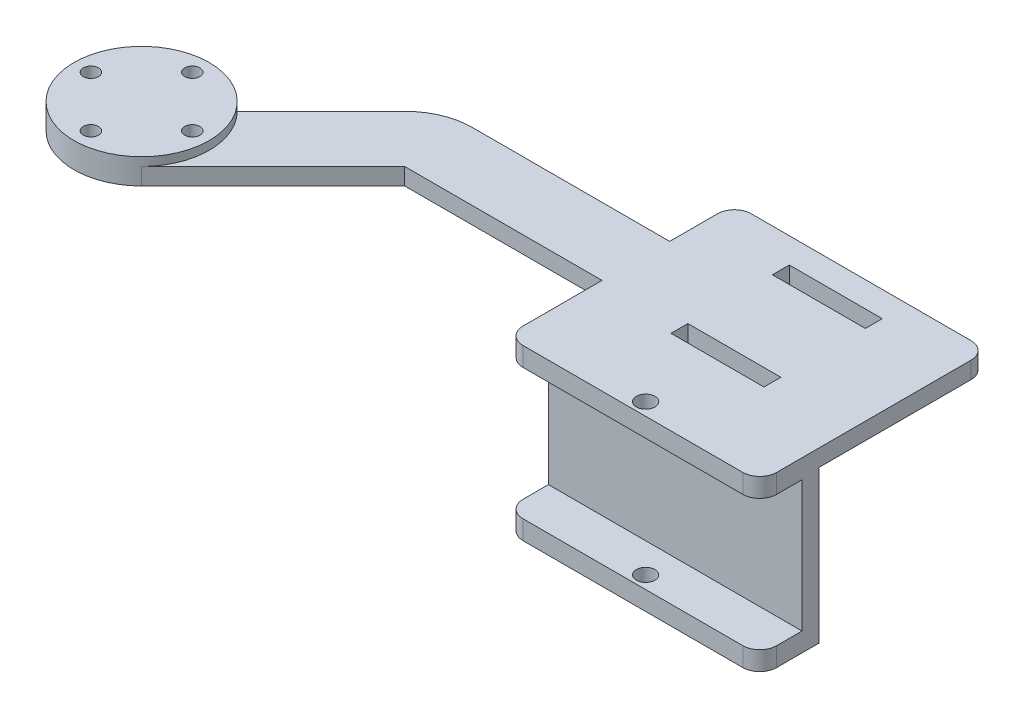
SolidWorks part; units mm, degrees
ref_plane "前视基准面" through (0, 0, 0) normal (0, 0, 1) x (1, 0, 0)
ref_plane "上视基准面" through (0, 0, 0) normal (0, 1, 0) x (1, 0, 0)
ref_plane "右视基准面" through (0, 0, 0) normal (1, 0, 0) x (0, 0, -1)
other "Configuration Table"
sketch "草图1" plane through (0, 0, 0) normal (0, 1, 0) x (1, 0, 0)
  line L1 (0, 0) -> (30, 0)
  line L2 (0, 0) -> (0, -7)
  line L3 (0, -7) -> (30, -7)
  line L4 (30, 0) -> (30, -7)
  dimension "D1" = 7
  dimension "D2" = 30
extrude "凸台-拉伸1" add sketch "草图1" along normal blind 20
sketch "草图2" plane through (0, 0, 7) normal (0, 0, 1) x (1, 0, 0)
  line L0 (0, 20) -> (0, 0) construction
  line L1 (0, 10) -> (6.5085, 10) construction
  line L2 (30, 20) -> (30, 0) construction
  line L3 (0, 17.75) -> (30, 17.75)
  line L4 (0, 17.75) -> (0, 2.25)
  line L5 (0, 2.25) -> (30, 2.25)
  line L6 (30, 17.75) -> (30, 2.25)
  line L7 (0, 17.75) -> (30, 2.25) construction
  point P4 (15, 10)
  point P12 (0, 10)
  dimension "D1" = 15.5
extrude "切除-拉伸1" cut sketch "草图2" against normal blind 5
sketch "草图4" plane through (0, 20, 0) normal (0, 1, 0) x (1, 0, 0)
  line L2 (0, -7) -> (30, -7) construction
  line L3 (30, 0) -> (0, 0) construction
  circle A3 centre (15, -5.5) radius 1.1
  point P0 (15, -7)
  point P1 (15, -5.5)
  dimension "D1" = 5.5
extrude "切除-拉伸2" cut sketch "草图4" against normal through all both and the other way through all
sketch "草图5" plane through (0, 0, 0) normal (0, 0, -1) x (-1, 0, 0)
  line L0 (-30, 20) -> (0, 20) construction
  line L1 (-30, 20) -> (0, 20)
  line L2 (-30, 20) -> (-30, 18)
  line L3 (-30, 18) -> (0, 18)
  line L4 (0, 20) -> (0, 18)
  line L5 (-30, 20) -> (-30, 0) construction
  line L6 (0, 20) -> (0, 0) construction
  dimension "D1" = 2
extrude "凸台-拉伸2" add sketch "草图5" along normal blind 20
sketch "草图6" plane through (0, 20, 0) normal (0, 1, 0) x (1, 0, 0)
  line L0 (0, 10) -> (30, 10) construction
  line L1 (0, 20) -> (0, -7) construction
  line L2 (30, -7) -> (30, 20) construction
  line L3 (0, 20) -> (30, 20) construction
  line L5 (9.5, 17) -> (20.5, 17)
  line L6 (9.5, 17) -> (9.5, 15)
  line L7 (9.5, 15) -> (20.5, 15)
  line L8 (20.5, 17) -> (20.5, 15)
  line L9 (9.5, 17) -> (20.5, 15) construction
  line L10 (9.5, 15) -> (20.5, 17) construction
  line L11 (9.5, 5) -> (20.5, 5)
  line L12 (9.5, 5) -> (9.5, 3)
  line L13 (9.5, 3) -> (20.5, 3)
  line L14 (20.5, 5) -> (20.5, 3)
  line L15 (9.5, 5) -> (20.5, 3) construction
  line L16 (9.5, 3) -> (20.5, 5) construction
  point P8 (15, 16)
  point P9 (15, 4)
  point P10 (15, 16)
  point P15 (15, 4)
  dimension "D1" = 10
  dimension "D2" = 6
  dimension "D3" = 6
  dimension "D4" = 2
  dimension "D5" = 11
  dimension "D6" = 11
  dimension "D7" = 2
extrude "切除-拉伸3" cut sketch "草图6" against normal up to surface (2 mm away) up to face at (15, 18, -10)
sketch "草图7" plane through (0, 18, 0) normal (0, -1, 0) x (1, 0, 0)
  line L0 (0, -20) -> (0, 0) construction
  line L1 (0, -10) -> (0, -12.3431)
  line L2 (0, -10) -> (0, -4.3431)
  line L3 (0, -10) -> (-29, -10) construction
  line L4 (-29, -10) -> (-44.5, -10) construction
  line L5 (-29, -10) -> (-23.3431, -4.3431) construction
  line L6 (0, -12.3431) -> (-23.3431, -12.3431)
  line L7 (0, -12.3431) -> (0, -4.3431)
  line L8 (0, -4.3431) -> (-23.3431, -4.3431)
  line L9 (-23.3431, -12.3431) -> (-23.3431, -4.3431) construction
  line L10 (-44.5, -10) -> (-44.5, 11.6178) construction
  line L11 (-23.3431, -4.3431) -> (-29, -10) construction
  line L12 (-23.3431, -4.3431) -> (-38.9075, 11.2212)
  line L13 (-29, -10) -> (-44.5644, 5.5644)
  line L14 (-38.9075, 11.2212) -> (-44.5644, 5.5644)
  arc A0 (-29, -10) -> (-23.3431, -12.3431) centre (-23.3431, -4.3431) ccw
  point P0 (0, -10)
  line M10 (0, 0) -> (0, -20)
  dimension "D2" = 29
  dimension "D1" = 8
  dimension "D3" = 45
  dimension "D4" = 15.5
extrude "凸台-拉伸3" add sketch "草图7" against normal up to surface (2 mm away) contours L13 A0 L6 L8 L12 L14 M10 up to face at (15, 20, -16)
sketch "草图8" plane through (0, 18, 0) normal (0, -1, 0) x (1, 0, 0)
  circle A0 centre (-44.5644, 5.5644) radius 8
extrude "凸台-拉伸4" add sketch "草图8" against normal blind 3
sketch "草图10" plane through (0, 21, 0) normal (0, 1, 0) x (1, 0, 0)
  circle A0 centre (-44.5644, -5.5644) radius 6 construction
  circle A1 centre (-44.5644, -5.5644) radius 8 construction
  circle A2 centre (-38.5644, -5.5644) radius 0.9
  circle A3 centre (-44.5644, -11.5644) radius 0.9
  circle A4 centre (-50.5644, -5.5644) radius 0.9
  circle A5 centre (-44.5644, 0.4356) radius 0.9
extrude "切除-拉伸4" cut sketch "草图10" against normal up to next
fillet "圆角1" radius 2 6 edges at (30, 19, -20) (0, 19, -20) (30, 18.875, 7) (30, 1.125, 7) (0, 1.125, 7) (0, 18.875, 7)
sketch "草图11" plane through (0, 21, 0) normal (0, 1, 0) x (1, 0, 0)
  point P0 (-44.5644, -11.5644)
  point P1 (-44.5644, -5.5644)
